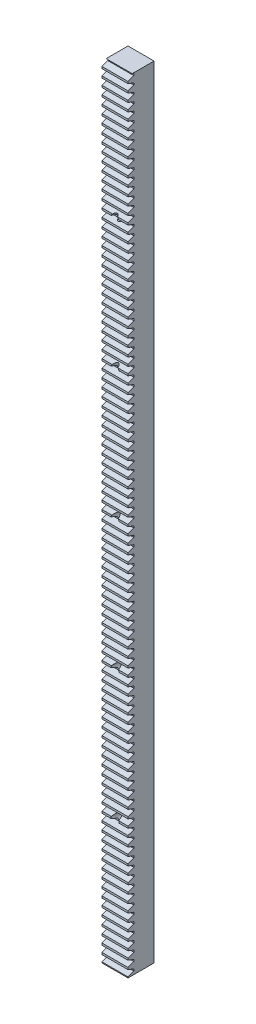
SolidWorks part; units mm, degrees
ref_plane "前视基准面" through (0, 0, 0) normal (0, 0, 1) x (1, 0, 0)
ref_plane "上视基准面" through (0, 0, 0) normal (0, 1, 0) x (1, 0, 0)
ref_plane "右视基准面" through (0, 0, 0) normal (1, 0, 0) x (0, 0, -1)
other "Configuration Table"
sketch "草图3" plane through (0, 0, 0) normal (0, 1, 0) x (1, 0, 0)
  line L1 (0, 0) -> (20, 0)
  line L2 (0, 0) -> (0, 20)
  line L3 (0, 20) -> (20, 20)
  line L4 (20, 0) -> (20, 20)
  dimension "D1" = 20
  dimension "D2" = 20
extrude "凸台-拉伸1" add sketch "草图3" along normal blind 600
sketch "草图4" plane through (0, 0, 0) normal (1, 0, 0) x (0, 0, -1)
  line L0 (-36.1119, 0) -> (48.2922, 0) construction
  line L1 (0, 0) -> (0, 0.7486)
  line L2 (0, 600) -> (0, 0) construction
  line L3 (0, 0.7486) -> (4.5, 2.3864)
  line L4 (4.5, 2.3864) -> (4.5, 3.8836)
  line L5 (4.5, 3.8836) -> (0, 5.5214)
  line L6 (0, 5.5214) -> (0, 6.27)
  line L7 (-6.5746, 3.135) -> (9.1145, 3.135) construction
  line L8 (2.25, 5.2351) -> (2.25, 0.4412) construction
  line L9 (0, 6.27) -> (-2, 6.27)
  line L10 (-2, 6.27) -> (-2, 0)
  line L11 (-2, 0) -> (0, 0)
  point P14 (2.25, 4.7025)
  point P15 (2.25, 1.5675)
  dimension "D1" = 6.27
  dimension "D2" = 4.5
  dimension "D3" = 2.25
  dimension "D4" = 3.135
  dimension "D5" = 20
  dimension "D6" = 2
extrude "切除-拉伸1" cut sketch "草图4" along normal up to next
pattern_linear "阵列(线性)1" count 96 spacing 6.27 along (0, 1, 0) of "切除-拉伸1"
sketch "草图5" plane through (0, 0, 0) normal (0, 1, 0) x (1, 0, 0)
  circle A0 centre (10, 10) radius 4
  dimension "D3" = 8
  dimension "D1" = 10
  dimension "D2" = 10
extrude "切除-拉伸2" cut sketch "草图5" along normal blind 20
sketch "草图6" plane through (0, 0, 0) normal (0, 0, 1) x (1, 0, 0)
  line L0 (10, -11.5623) -> (10, 414.8088) construction
  line L1 (10, 100) -> (10, 200) construction
  circle A0 centre (10, 100) radius 3
  circle A1 centre (10, 200) radius 3
  circle A2 centre (10, 300) radius 3
  circle A3 centre (10, 400) radius 3
  circle A4 centre (10, 500) radius 3
  dimension "D2" = 6
  dimension "D1" = 10
  dimension "D3" = 100
  dimension "D5" = 100
  dimension "D4" = 5
extrude "切除-拉伸3" cut sketch "草图6" against normal through all
